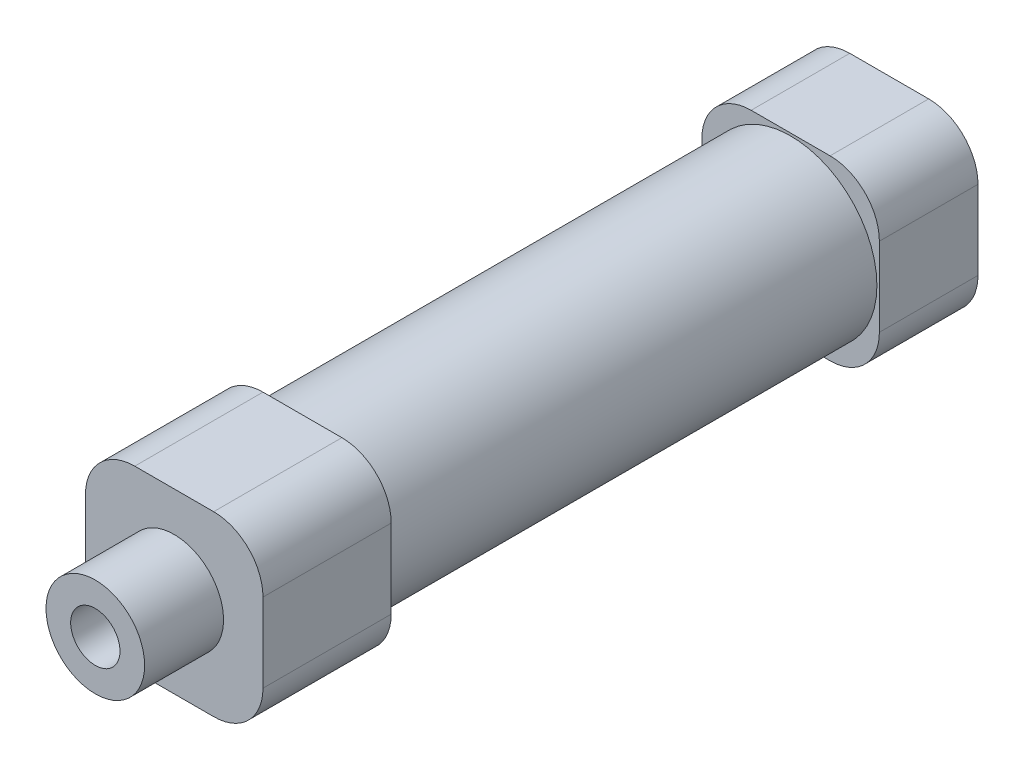
SolidWorks part; units mm, degrees
ref_plane "前视基准面" through (0, 0, 0) normal (0, 0, 1) x (1, 0, 0)
ref_plane "上视基准面" through (0, 0, 0) normal (0, 1, 0) x (1, 0, 0)
ref_plane "右视基准面" through (0, 0, 0) normal (1, 0, 0) x (0, 0, -1)
sketch "草图1" plane through (0, 0, 0) normal (0, 0, 1) x (1, 0, 0)
  line L1 (-9, 9) -> (9, 9)
  line L2 (-9, 9) -> (-9, -9)
  line L3 (-9, -9) -> (9, -9)
  line L4 (9, 9) -> (9, -9)
  line L5 (-9, 9) -> (9, -9) construction
  line L6 (-9, -9) -> (9, 9) construction
  point P0 (0, 0)
  dimension "D1" = 18
  dimension "D2" = 18
extrude "凸台-拉伸1" add sketch "草图1" along normal blind 10
sketch "草图2" plane through (0, 0, 10) normal (0, 0, 1) x (1, 0, 0)
  line L0 (0, 9) -> (0, -9) construction
  line L1 (9, 9) -> (-9, 9) construction
  line L2 (-9, -9) -> (9, -9) construction
  circle A0 centre (0, 0) radius 8.75
  dimension "D1" = 17.5
extrude "凸台-拉伸2" add sketch "草图2" along normal blind 49.5
sketch "草图3" plane through (0, 0, 59.5) normal (0, 0, 1) x (1, 0, 0)
  line L1 (-9, -9) -> (9, -9)
  line L2 (-9, -9) -> (-9, 9)
  line L3 (-9, 9) -> (9, 9)
  line L4 (9, -9) -> (9, 9)
  line L5 (-9, -9) -> (9, 9) construction
  line L6 (-9, 9) -> (9, -9) construction
  point P0 (0, 0)
extrude "凸台-拉伸3" add sketch "草图3" along normal blind 13
sketch "草图4" plane through (0, 0, 72.5) normal (0, 0, 1) x (1, 0, 0)
  circle A0 centre (0, 0) radius 5
  dimension "D1" = 10
extrude "凸台-拉伸4" add sketch "草图4" along normal blind 8
cosmetic thread "装饰螺纹线1" parameters "D2"=6.941
sketch "草图5" plane through (0, 0, 80.5) normal (0, 0, 1) x (1, 0, 0)
  circle A0 centre (0, 0) radius 2.5
  dimension "D1" = 5
extrude "切除-拉伸1" cut sketch "草图5" against normal offset from surface (79.5 mm away) 1 up to face at (0, 0, 0)
fillet "圆角1" radius 5 8 edges at (-9, 9, 66) (-9, -9, 66) (9, -9, 5) (9, -9, 66) (9, 9, 5) (9, 9, 66) (-9, 9, 5) (-9, -9, 5)
sketch "草图6" plane through (0, -9, 0) normal (0, -1, 0) x (1, 0, 0)
  line L0 (4, 5.25) -> (-4, 5.25) construction
  line L1 (4, 0) -> (4, 10) construction
  line L2 (-4, 10) -> (-4, 0) construction
  line L3 (-4, 10) -> (4, 10) construction
  line L4 (4, 64.25) -> (-4, 64.25) construction
  line L5 (4, 59.5) -> (4, 72.5) construction
  line L6 (-4, 72.5) -> (-4, 59.5) construction
  line L8 (-4, 59.5) -> (4, 59.5) construction
  circle A0 centre (0, 5.25) radius 2.5
  circle A1 centre (0, 64.25) radius 2.5
  dimension "D2" = 5
  dimension "D4" = 5
  dimension "D1" = 4.75
  dimension "D3" = 4.75
extrude "切除-拉伸2" cut sketch "草图6" against normal up to surface (9 mm away) up to plane "上视基准面"
